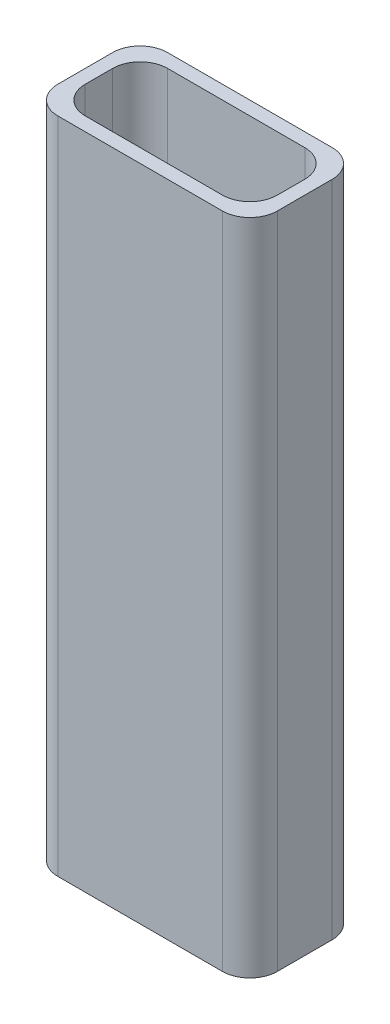
SolidWorks part; units mm, degrees
ref_plane "Front Plane" through (0, 0, 0) normal (0, 0, 1) x (1, 0, 0)
ref_plane "Top Plane" through (0, 0, 0) normal (0, 1, 0) x (1, 0, 0)
ref_plane "Right Plane" through (0, 0, 0) normal (1, 0, 0) x (0, 0, -1)
sketch "Sketch1" plane through (0, 0, 0) normal (0, 1, 0) x (1, 0, 0)
  line L1 (15, -10) -> (-15, -10)
  line L2 (20, -5) -> (20, 5)
  line L3 (15, 10) -> (-15, 10)
  line L4 (-20, -5) -> (-20, 5)
  line L5 (20, -10) -> (-20, 10) construction
  line L6 (20, 10) -> (-20, -10) construction
  arc A0 (-15, 10) -> (-20, 5) centre (-15, 5) ccw
  arc A1 (-15, -10) -> (-20, -5) centre (-15, -5) cw
  arc A2 (15, -10) -> (20, -5) centre (15, -5) ccw
  arc A3 (20, 5) -> (15, 10) centre (15, 5) ccw
  point P0 (0, 0)
  dimension "D3" = 5
  dimension "D1" = 20
  dimension "D2" = 40
extrude "Boss-Extrude2" add sketch "Sketch1" along normal mid plane 120
sketch "Sketch3" plane through (0, 60, 0) normal (0, 1, 0) x (1, 0, 0)
  line L1 (12.5, -7.5) -> (-12.5, -7.5)
  line L2 (17.5, -2.5) -> (17.5, 2.5)
  line L3 (12.5, 7.5) -> (-12.5, 7.5)
  line L4 (-17.5, -2.5) -> (-17.5, 2.5)
  line L5 (17.5, -7.5) -> (-17.5, 7.5) construction
  line L6 (17.5, 7.5) -> (-17.5, -7.5) construction
  arc A0 (-12.5, 7.5) -> (-17.5, 2.5) centre (-12.5, 2.5) ccw
  arc A1 (-12.5, -7.5) -> (-17.5, -2.5) centre (-12.5, -2.5) cw
  arc A2 (12.5, -7.5) -> (17.5, -2.5) centre (12.5, -2.5) ccw
  arc A3 (17.5, 2.5) -> (12.5, 7.5) centre (12.5, 2.5) ccw
  point P0 (0, 0)
  dimension "D3" = 5
  dimension "D1" = 35
  dimension "D2" = 15
extrude "Cut-Extrude2" cut sketch "Sketch3" against normal through all
sketch "Sketch4" plane through (0, 0, -10) normal (0, 0, -1) x (-1, 0, 0)
  line L0 (0, 45) -> (0, -45) construction
  line L1 (6, 45) -> (6, -45)
  line L2 (-6, 45) -> (-6, -45)
  arc A0 (6, 45) -> (-6, 45) centre (0, 45) ccw
  arc A1 (-6, -45) -> (6, -45) centre (0, -45) ccw
  point P2 (0, 0)
  dimension "D1" = 6
  dimension "D2" = 90
extrude "Cut-Extrude3" [suppressed] cut sketch "Sketch4" against normal through all
